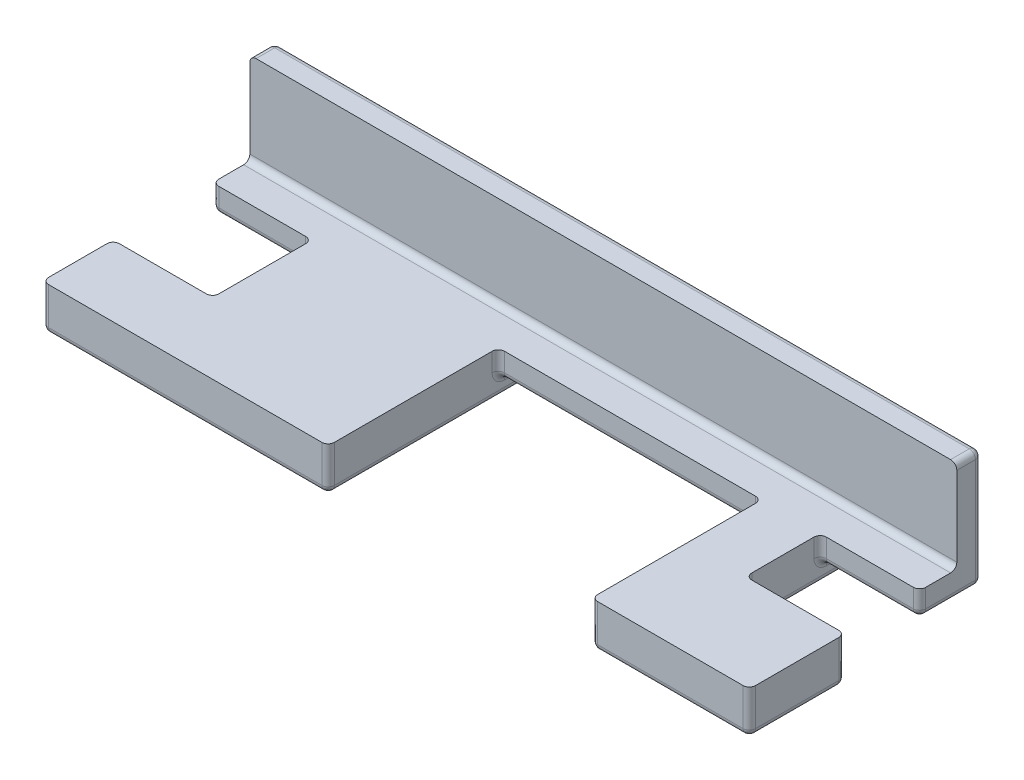
SolidWorks part; units mm, degrees
ref_plane "Front Plane" through (0, 0, 0) normal (0, 0, 1) x (1, 0, 0)
ref_plane "Top Plane" through (0, 0, 0) normal (0, 1, 0) x (1, 0, 0)
ref_plane "Right Plane" through (0, 0, 0) normal (1, 0, 0) x (0, 0, -1)
sketch "Sketch1" plane through (0, 0, 0) normal (1, 0, 0) x (0, 0, -1)
  line L0 (3.6, 4.9) -> (1.6, 4.9) construction
  line L1 (1.6, 9.5) -> (1.6, -2.5) construction
  line L2 (3.6, -4.5) -> (3.6, 4.9) construction
  line L3 (-1.4, -4.5) -> (3.6, -4.5) construction
  line L4 (-1.4, -2.5) -> (-1.4, -4.5) construction
  line L5 (-27.5, -2.5) -> (1.6, -2.5) construction
  line L6 (3.6, 4.9) -> (1.6, 4.9)
  line L7 (1.6, 9.5) -> (1.6, -2.5)
  line L8 (3.6, -4.5) -> (3.6, 4.9)
  line L9 (-1.4, -4.5) -> (3.6, -4.5)
  line L10 (-1.4, -2.5) -> (-1.4, -4.5)
  line L11 (-27.5, -2.5) -> (1.6, -2.5)
extrude "Boss-Extrude1" add sketch "Sketch1" along normal up to surface (66.8 mm away) from surface contours L11 L10 L9 L8 L6 L7
sketch "Sketch3" plane through (0, -2.5, 0) normal (0, 1, 0) x (1, 0, 0)
  line L1 (-5.9, 1.6) -> (66.1, 1.6) construction
  line L2 (17.9, -1.9) -> (17.9, -8.9) construction
  line L3 (32.9, -14.6) -> (32.9, -1.9) construction
  line L4 (17.9, 3.6) -> (17.9, -9.4)
  line L5 (32.9, -15.1) -> (32.9, 3.6)
  line L6 (14.4, -15.1) -> (30.4, -15.1) construction
  line L7 (9.9, -15.1) -> (32.9, -15.1)
  line L9 (54.1, -1.9) -> (54.1, -8.9) construction
  line L10 (58.8, -14.0764) -> (58.8, -2.1) construction
  line L11 (17.4, -9.4) -> (10.4, -9.4) construction
  line L12 (54.1, 3.6) -> (54.1, -15.1)
  line L13 (58.8, -7.4) -> (58.8, 3.6)
  line L14 (17.9, -9.4) -> (9.9, -9.4)
  line L16 (9.9, 3.6) -> (9.9, -1.4) construction
  line L17 (9.9, -9.4) -> (9.9, -15.1)
  line L18 (54.1, -15.1) -> (66.8, -15.1)
  line L19 (58.8, -7.4) -> (66.8, -7.4)
  line L20 (66.8, -7.4) -> (66.8, -15.1)
  line L21 (66.8, 1.6) -> (66.8, 3.6) construction
  line L22 (66.8, 3.6) -> (9.9, 3.6) construction
  line L23 (66.8, 3.6) -> (9.9, 3.6)
  line M2 (66.8, 1.6) -> (9.9, 1.6)
  line M4 (9.9, -1.4) -> (66.8, -1.4)
  dimension "D1" = 9
extrude "Boss-Extrude2" add sketch "Sketch3" against normal up to surface (3.5 mm away) contours L14 L17 L7 L5 L4 M4 | L20 L19 L13 L12 L18 M4 | L5 L4 M4 M2 | L13 L12 M4 M2 | L5 L23 L4 M2 | L13 L23 L12 M2
fillet "Fillet1" radius 0.5 48 edges at (9.9, 0.2, -3.6) (66.8, 0.2, -3.6) (38.35, 4.9, -3.6) (9.9, -4.5, -1.1) (13.9, -4.5, 1.4) (17.9, -6, 2.9) (13.9, -6, 9.4) (9.9, -6, 12.25) (21.4, -6, 15.1) (32.9, -6, 5.75) (43.5, -4.5, 1.4) (54.1, -6, 5.75) (60.45, -6, 15.1) (66.8, -6, 11.25) (62.8, -6, 7.4) (58.8, -6, 1.9) (62.8, -4.5, 1.4) (66.8, -4.5, -1.1) (62.8, -4.5, -3.6) (13.9, -4.5, -3.6) (58.8, -4.25, 7.4) (58.8, -3.5, 1.4) (66.8, 4.9, -2.6) (66.8, -3.5, 1.4) (66.8, -4.25, 7.4) (66.8, -4.25, 15.1) (54.1, -4.25, 15.1) (54.1, -3.5, 1.4) (32.9, -3.5, 1.4) (32.9, -4.25, 15.1) (9.9, -4.25, 15.1) (9.9, -4.25, 9.4) (17.9, -4.25, 9.4) (17.9, -3.5, 1.4) (9.9, -3.5, 1.4) (9.9, 4.9, -2.6) (38.35, -2.5, -1.6) (17.9, -5.25, -3.6) (25.4, -6, -3.6) (32.9, -5.25, -3.6) (43.5, -4.5, -3.6) (54.1, -5.25, -3.6) (56.45, -6, -3.6) (58.8, -5.25, -3.6) (58.8, -4.5, -1.1) (17.9, -4.5, -1.1) (32.9, -4.5, -1.1) (54.1, -4.5, -1.1)
